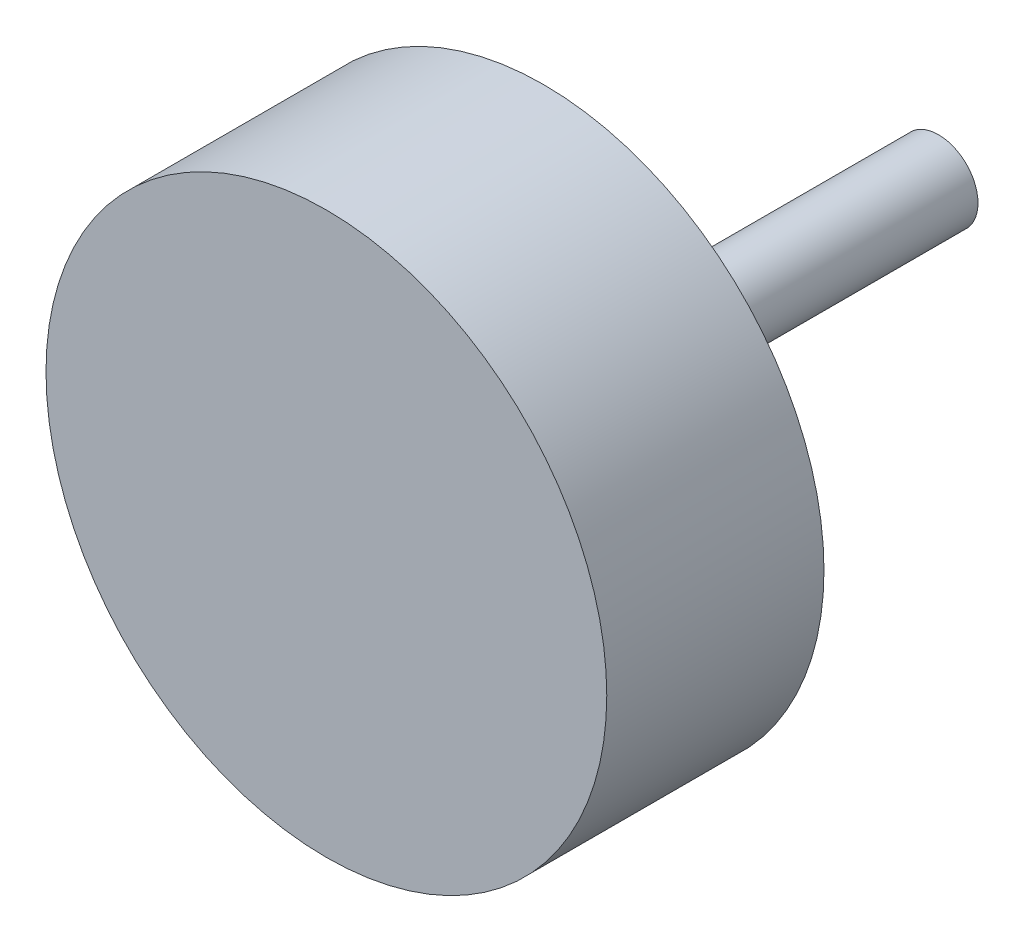
SolidWorks part; units mm, degrees
material "Gray Cast Iron"
ref_plane "Alzado" through (0, 0, 0) normal (0, 0, 1) x (1, 0, 0)
ref_plane "Planta" through (0, 0, 0) normal (0, 1, 0) x (1, 0, 0)
ref_plane "Vista lateral" through (0, 0, 0) normal (1, 0, 0) x (0, 0, -1)
sketch "Sketch1" plane through (0, 0, 0) normal (0, 0, 1) x (1, 0, 0)
  circle A0 centre (0, 0) radius 7.1
  dimension "D1" = 14.2
extrude "Boss-Extrude1" add sketch "Sketch1" along normal blind 5.5
sketch "Sketch2" plane through (0, 0, 0) normal (0, 0, -1) x (-1, 0, 0)
  circle A0 centre (0, 0) radius 1
  dimension "D1" = 2
extrude "Boss-Extrude2" add sketch "Sketch2" along normal blind 10
